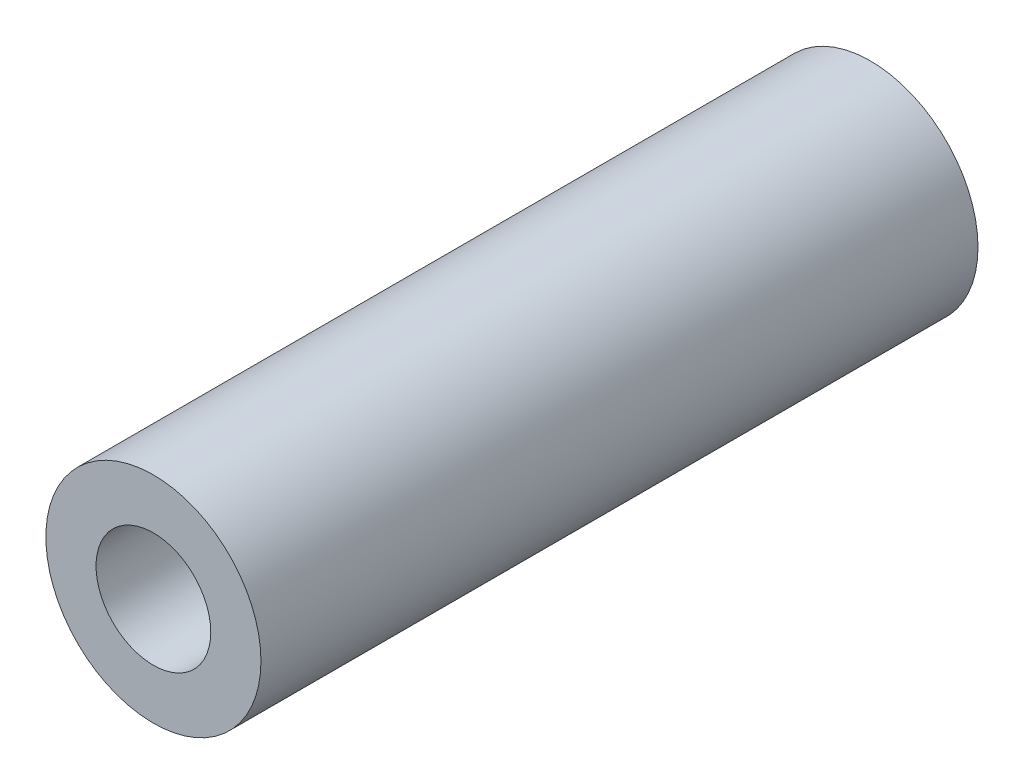
SolidWorks part; units mm, degrees
ref_plane "정면" through (0, 0, 0) normal (0, 0, 1) x (1, 0, 0)
ref_plane "윗면" through (0, 0, 0) normal (0, 1, 0) x (1, 0, 0)
ref_plane "우측면" through (0, 0, 0) normal (1, 0, 0) x (0, 0, -1)
sketch "스케치1" plane through (0, 0, 0) normal (0, 0, 1) x (1, 0, 0)
  circle A0 centre (0, 0) radius 7.5
  dimension "D1" = 15
extrude "보스-돌출1" add sketch "스케치1" along normal blind 50
sketch "스케치2" plane through (0, 0, 50) normal (0, 0, 1) x (1, 0, 0)
  circle A0 centre (0, 0) radius 4
  dimension "D1" = 8
extrude "컷-돌출1" cut sketch "스케치2" against normal blind 30
